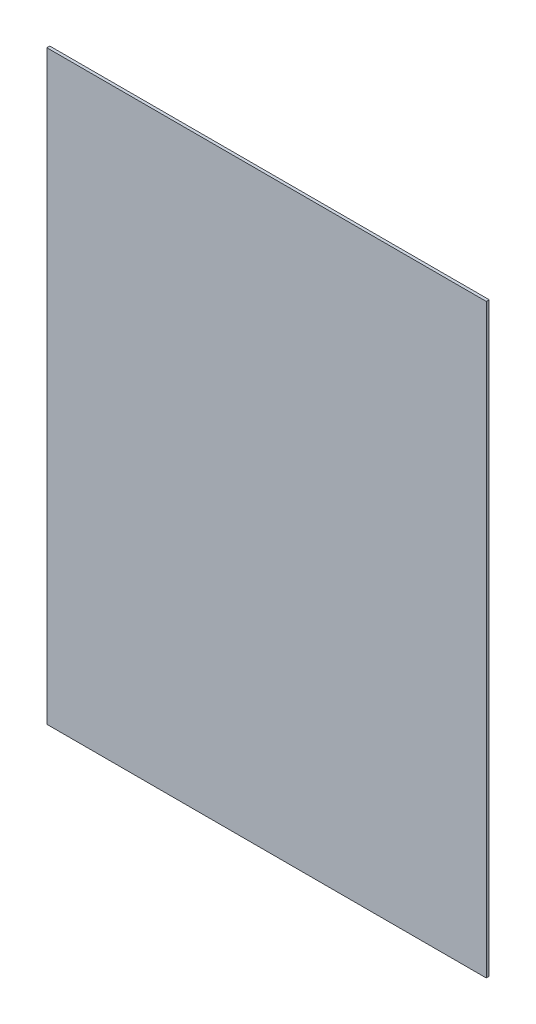
SolidWorks part; units mm, degrees
ref_plane "Front Plane" through (0, 0, 0) normal (0, 0, 1) x (1, 0, 0)
ref_plane "Top Plane" through (0, 0, 0) normal (0, 1, 0) x (1, 0, 0)
ref_plane "Right Plane" through (0, 0, 0) normal (1, 0, 0) x (0, 0, -1)
sketch "Sketch1" plane through (0, 0, 0) normal (0, 0, 1) x (1, 0, 0)
  line L2 (-341.4634, 254.3554) -> (-41.4634, 254.3554)
  line L3 (-341.4634, 254.3554) -> (-341.4634, -145.6446)
  line L4 (-341.4634, -145.6446) -> (-41.4634, -145.6446)
  line L5 (-41.4634, 254.3554) -> (-41.4634, -145.6446)
  dimension "D1" = 400
  dimension "D2" = 300
extrude "Boss-Extrude1" add sketch "Sketch1" along normal blind 2
